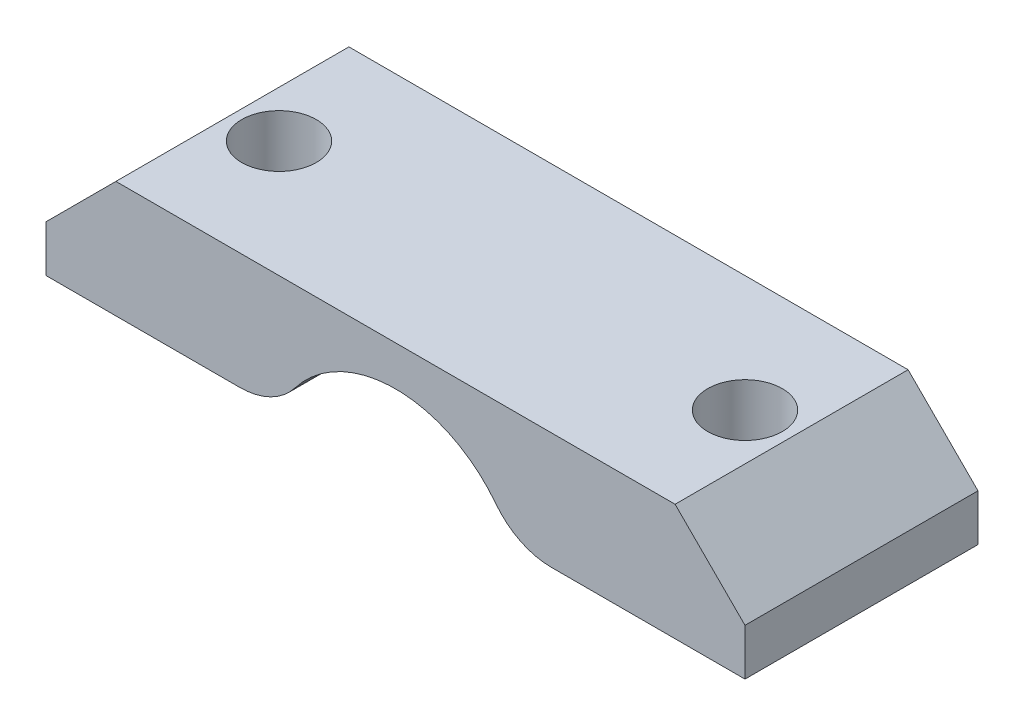
SolidWorks part; units mm, degrees
ref_plane "Ebene vorne" through (0, 0, 0) normal (0, 0, 1) x (1, 0, 0)
ref_plane "Ebene oben" through (0, 0, 0) normal (0, 1, 0) x (1, 0, 0)
ref_plane "Ebene rechts" through (0, 0, 0) normal (1, 0, 0) x (0, 0, -1)
sketch "Skizze3" plane through (0, 0, 0) normal (0, 0, 1) x (1, 0, 0)
  line L0 (0, 0) -> (0, 5)
  line L1 (0, 5) -> (30, 5)
  line L2 (0, 0) -> (10, 0)
  line L3 (30, 5) -> (30, 0)
  line L4 (30, 0) -> (20, 0)
  arc A0 (10, 0) -> (20, 0) centre (15, -2.1549) cw
extrude "Aufsatz-Linear austragen1" add sketch "Skizze3" along normal blind 10
sketch "Skizze4" plane through (0, 5, 0) normal (0, 1, 0) x (1, 0, 0)
  circle A0 centre (5, -5) radius 1.6
  circle A1 centre (25, -5) radius 1.6
extrude "Schnitt-Linear austragen1" cut sketch "Skizze4" against normal blind 10
chamfer "Fase1" distance 3 angle 45 2 edges at (30, 5, 5) (0, 5, 5)
fillet "Verrundung1" radius 3 2 edges at (20, 0, 5) (10, 0, 5)
